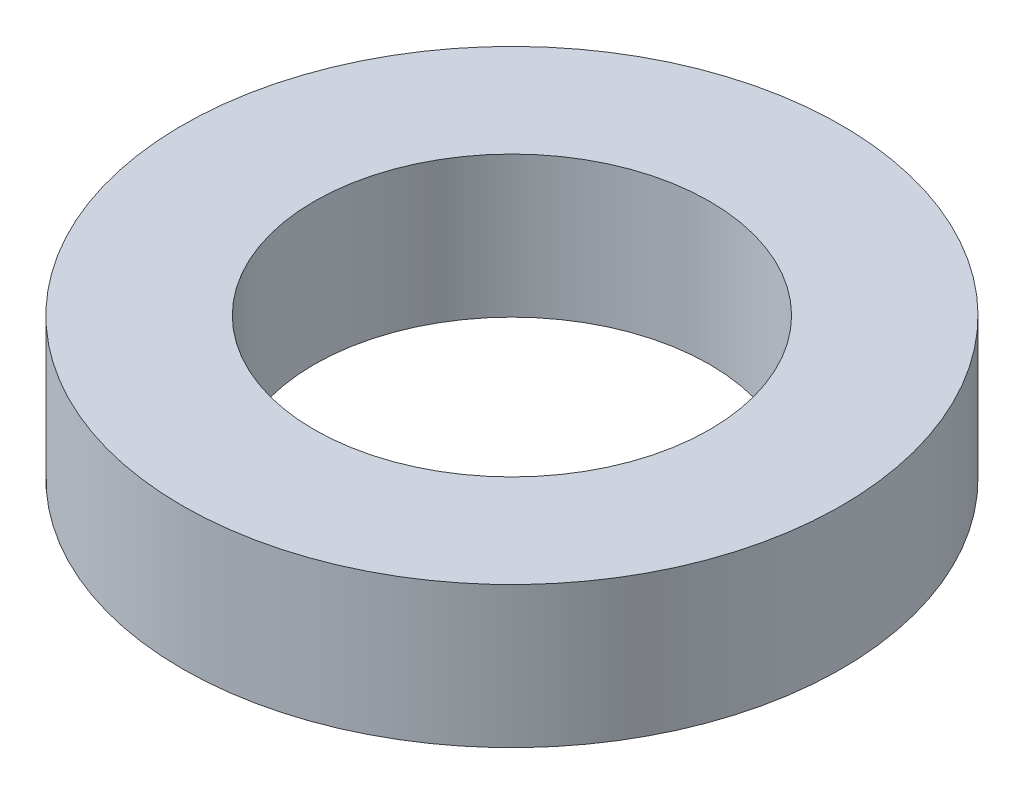
SolidWorks part; units mm, degrees
ref_plane "前视基准面" through (0, 0, 0) normal (0, 0, 1) x (1, 0, 0)
ref_plane "上视基准面" through (0, 0, 0) normal (0, 1, 0) x (1, 0, 0)
ref_plane "右视基准面" through (0, 0, 0) normal (1, 0, 0) x (0, 0, -1)
other "Configuration Table"
sketch "草图1" plane through (0, 0, 0) normal (0, 1, 0) x (1, 0, 0)
  circle A0 centre (0, 0) radius 2.1
  circle A1 centre (0, 0) radius 3.5
  dimension "D1" = 4.2
  dimension "D2" = 7
extrude "凸台-拉伸1" add sketch "草图1" along normal blind 1.5 contours A1 A0
